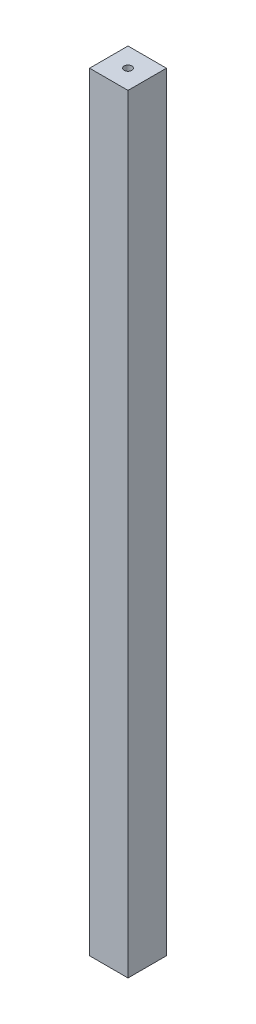
SolidWorks part; units mm, degrees
ref_plane "Спереди" through (0, 0, 0) normal (0, 0, 1) x (1, 0, 0)
ref_plane "Сверху" through (0, 0, 0) normal (0, 1, 0) x (1, 0, 0)
ref_plane "Справа" through (0, 0, 0) normal (1, 0, 0) x (0, 0, -1)
other "Configuration Table"
sketch "Эскиз1" plane through (0, 0, 0) normal (0, 1, 0) x (1, 0, 0)
  line L1 (25, 25) -> (-25, 25)
  line L2 (25, 25) -> (25, -25)
  line L3 (25, -25) -> (-25, -25)
  line L4 (-25, 25) -> (-25, -25)
  line L5 (25, 25) -> (-25, -25) construction
  line L6 (25, -25) -> (-25, 25) construction
  point P0 (0, 0)
extrude "Бобышка-Вытянуть2" add sketch "Эскиз1" along normal blind 900 contours L4 L3 L2 L1
sketch "Эскиз4" plane through (0, 900, 0) normal (0, 1, 0) x (1, 0, 0)
  circle A0 centre (0, 0) radius 5
extrude "Вырез-Вытянуть2" cut sketch "Эскиз4" against normal blind 50
sketch "Эскиз5" plane through (0, 0, 0) normal (0, -1, 0) x (1, 0, 0)
  circle A0 centre (0, 0) radius 5
extrude "Вырез-Вытянуть3" cut sketch "Эскиз5" against normal blind 50
sketch "Эскиз6" plane through (0, 0, 0) normal (0, -1, 0) x (1, 0, 0)
  line L4 (-25, -25) -> (25, -25)
  line L5 (25, -25) -> (25, 25)
  line L6 (25, 25) -> (-25, 25)
  line L7 (-25, 25) -> (-25, -25)
  line L8 (-25, -25) -> (25, -25)
  line L9 (25, -25) -> (25, 25)
  line L10 (25, 25) -> (-25, 25)
  line L11 (-25, 25) -> (-25, -25)
  dimension "D1" = 0
extrude "Бобышка-Вытянуть3" add sketch "Эскиз6" along normal blind 100
sketch "Эскиз7" plane through (0, -100, 0) normal (0, -1, 0) x (1, 0, 0)
  circle A0 centre (0, 0) radius 5
extrude "Вырез-Вытянуть4" cut sketch "Эскиз7" against normal blind 100
